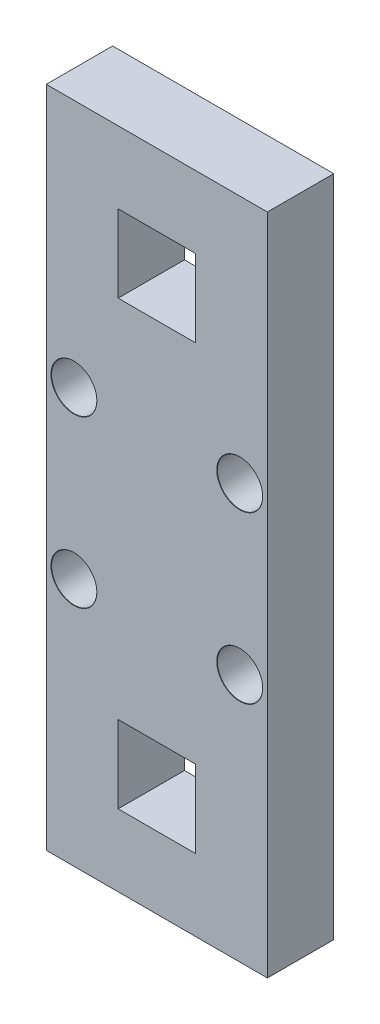
SolidWorks part; units mm, degrees
material "ABS"
ref_plane "前视基准面" through (0, 0, 0) normal (0, 0, 1) x (1, 0, 0)
ref_plane "上视基准面" through (0, 0, 0) normal (0, 1, 0) x (1, 0, 0)
ref_plane "右视基准面" through (0, 0, 0) normal (1, 0, 0) x (0, 0, -1)
other "Configuration Table"
sketch "草图1" plane through (0, 0, 0) normal (0, 0, 1) x (1, 0, 0)
  line L1 (-10, -30) -> (10, -30)
  line L2 (-10, -30) -> (-10, 30)
  line L3 (-10, 30) -> (10, 30)
  line L4 (10, -30) -> (10, 30)
  line L5 (-10, -30) -> (10, 30) construction
  line L6 (-10, 30) -> (10, -30) construction
  point P0 (0, 0)
  dimension "D1" = 20
  dimension "D2" = 60
extrude "凸台-拉伸1" add sketch "草图1" along normal blind 6
sketch "草图2" plane through (0, 0, 6) normal (0, 0, 1) x (1, 0, 0)
  line L0 (0, 30) -> (0, 20)
  line L1 (10, 30) -> (-10, 30) construction
  line L5 (-3.5, 23.5) -> (3.5, 23.5)
  line L6 (-3.5, 23.5) -> (-3.5, 16.5)
  line L7 (-3.5, 16.5) -> (3.5, 16.5)
  line L8 (3.5, 23.5) -> (3.5, 16.5)
  line L9 (-3.5, 23.5) -> (3.5, 16.5) construction
  line L10 (-3.5, 16.5) -> (3.5, 23.5) construction
  dimension "D1" = 10
  dimension "D2" = 7
  dimension "D3" = 7
extrude "切除-拉伸1" cut sketch "草图2" against normal blind 10
mirror "镜向1" about plane through (0, 0, 0) normal (0, 1, 0) of "切除-拉伸1"
sketch "草图3" plane through (0, 0, 6) normal (0, 0, 1) x (1, 0, 0)
  line L1 (-7.5, -7.5) -> (7.5, -7.5) construction
  line L2 (-7.5, -7.5) -> (-7.5, 7.5) construction
  line L3 (-7.5, 7.5) -> (7.5, 7.5) construction
  line L4 (7.5, -7.5) -> (7.5, 7.5) construction
  line L5 (-7.5, -7.5) -> (7.5, 7.5) construction
  line L6 (-7.5, 7.5) -> (7.5, -7.5) construction
  point P0 (0, 0)
  dimension "D1" = 15
  dimension "D2" = 15
hole_wizard "Ø4.1 (4.1) 直径孔1" positions "3D草图2" profile "草图5" hole size "Ø4.1" standard "GB" end condition through all
sketch3d "3D草图2"
  point P0 (-7.5, 7.5, 6)
  point P3 (7.5, 7.5, 6)
  point P6 (7.5, -7.5, 6)
  point P9 (-7.5, -7.5, 6)
sketch "草图5" plane through (-7.5, 7.5, 6) normal (1, 0, 0) x (0, -1, 0)
  line L0 (0, 0) -> (0, 6)
  line L1 (0, 6) -> (2.05, 6)
  line L2 (2.05, 6) -> (2.05, 0.025)
  line L3 (2.05, 0.025) -> (2.075, 0)
  line L5 (2.075, 0) -> (0, 0)
  line L6 (-2.05, 0.025) -> (-2.075, 0) construction
  line L11 (0, -6.35) -> (0, 107.95) construction
  dimension "通孔孔直径" = 4.1
  dimension "通孔孔深度" = 6
  dimension "近端锥形沉头孔直径" = 4.15
  dimension "近端锥形沉头孔角度" = 90
